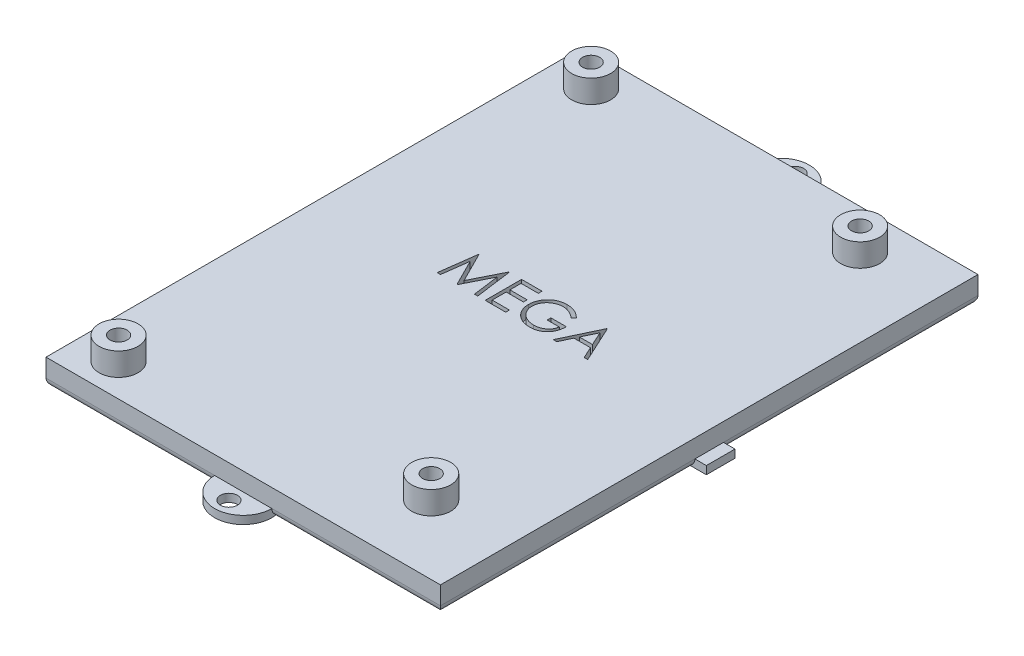
SolidWorks part; units mm, degrees
ref_plane "Front Plane" through (0, 0, 0) normal (0, 0, 1) x (1, 0, 0)
ref_plane "Top Plane" through (0, 0, 0) normal (0, 1, 0) x (1, 0, 0)
ref_plane "Right Plane" through (0, 0, 0) normal (1, 0, 0) x (0, 0, -1)
sketch "Sketch1" plane through (0, 0, 0) normal (0, 1, 0) x (1, 0, 0)
  line L0 (-34.45, 46.95) -> (34.45, 46.95)
  line L5 (-34.45, 46.95) -> (-34.45, -46.95)
  line L6 (-34.45, -46.95) -> (34.45, -46.95)
  line L7 (34.45, 46.95) -> (34.45, -46.95)
  point P11 (-34.45, 0)
  point P12 (0, -46.95)
  dimension "D3" = 93.9
  dimension "D4" = 68.9
extrude "Boss-Extrude1" add sketch "Sketch1" along normal blind 4.575
sketch "Sketch2" plane through (0, 4.575, 0) normal (0, 1, 0) x (1, 0, 0)
  line L0 (-27.45, 41.275) -> (20.81, 41.275) construction
  line L1 (-27.45, 41.275) -> (-27.45, -41.275) construction
  line L2 (20.81, 41.275) -> (20.81, 40.005) construction
  line L3 (20.81, -34.925) -> (-27.45, -34.925) construction
  line L4 (-34.45, 46.95) -> (-34.45, -46.95) construction
  line L6 (20.81, 40.005) -> (20.81, -34.925) construction
  circle A8 centre (-27.45, 41.275) radius 3.405
  circle A9 centre (-27.45, -41.275) radius 3.405
  circle A10 centre (20.81, -34.925) radius 3.405
  circle A11 centre (20.81, 40.005) radius 3.405
  circle A12 centre (-27.45, -41.275) radius 1.5
  circle A13 centre (-27.45, 41.275) radius 1.5
  circle A14 centre (20.81, 40.005) radius 1.5
  circle A15 centre (20.81, -34.925) radius 1.5
  point P3 (-27.45, 0)
  point P18 (-27.6001, -41.3408)
  dimension "D7" = 7
  dimension "D6" = 74.93
  dimension "D2" = 3
  dimension "D5" = 1.905
  dimension "D1" = 82.55
  dimension "D3" = 1.27
  dimension "D4" = 48.26
extrude "Boss-Extrude2" add sketch "Sketch2" along normal blind 4
sketch "Sketch3" plane through (0, 4.575, 0) normal (0, 1, 0) x (1, 0, 0)
  circle A4 centre (-27.45, -41.275) radius 1.5 construction
  circle A6 centre (-27.45, 41.275) radius 1.5
  circle A7 centre (20.81, 40.005) radius 1.5
  circle A8 centre (20.81, -34.925) radius 1.5
  circle A9 centre (-27.45, -41.275) radius 1.5
extrude "Cut-Extrude1" cut sketch "Sketch3" against normal offset from surface (3.575 mm away) 1 up to face at (0, 0, 0)
sketch "Sketch4" plane through (0, 0, 0) normal (0, 1, 0) x (1, 0, 0)
  line L0 (-5, -46.95) -> (5, -46.95)
  line L3 (-34.45, -46.95) -> (34.45, -46.95) construction
  line L4 (0, -46.95) -> (0, -51.95) construction
  arc A0 (-5, -46.95) -> (5, -46.95) centre (0, -46.95) ccw
  circle A2 centre (0, -49.45) radius 1.5
  point P6 (0, -46.95)
  dimension "D2" = 3
  dimension "D3" = 5
extrude "Boss-Extrude3" add sketch "Sketch4" along normal blind 1.4
mirror "Mirror1" about plane through (0, 0, 0) normal (0, 0, 1) of "Boss-Extrude3"
sketch "Sketch5" plane through (0, 4.575, 0) normal (0, 1, 0) x (1, 0, 0)
  line L0 (-15, 0) -> (15, 0) construction
  text T0 "MEGA\r\n" font "Century Gothic" height in points 24
  point P6 (0, 0)
  dimension "D1" = 30
extrude "Cut-Extrude2" cut sketch "Sketch5" against normal blind 2
sketch "Sketch6" plane through (-34.45, 0, 0) normal (-1, 0, 0) x (0, 0, 1)
  line L0 (-46.95, 0) -> (46.95, 0) construction
  line L1 (-2.5, 0) -> (2.5, 0)
  line L2 (-2.5, 0) -> (-2.5, 1.4)
  line L3 (-2.5, 1.4) -> (2.5, 1.4)
  line L4 (2.5, 0) -> (2.5, 1.4)
  line L5 (51.95, 1.4) -> (46.95, 1.4) construction
  point P6 (0, 0)
  point P7 (0, 1.4)
  dimension "D1" = 5
extrude "Boss-Extrude4" add sketch "Sketch6" along normal blind 2
mirror "Mirror2" about plane through (0, 0, 0) normal (1, 0, 0) of "Boss-Extrude4"
fillet "Fillet1" radius 1.4 16 edges at (-34.45, 0, 24.725) (-34.45, 0.7, -2.5) (-34.45, 0.7, 2.5) (34.45, 0, -24.725) (34.45, 0.7, -2.5) (34.45, 0.7, 2.5) (19.725, 0, -46.95) (34.45, 0, 24.725) (19.725, 0, 46.95) (-19.725, 0, 46.95) (-5, 0.7, 46.95) (5, 0.7, 46.95) (-34.45, 0, -24.725) (-19.725, 0, -46.95) (5, 0.7, -46.95) (-5, 0.7, -46.95)
